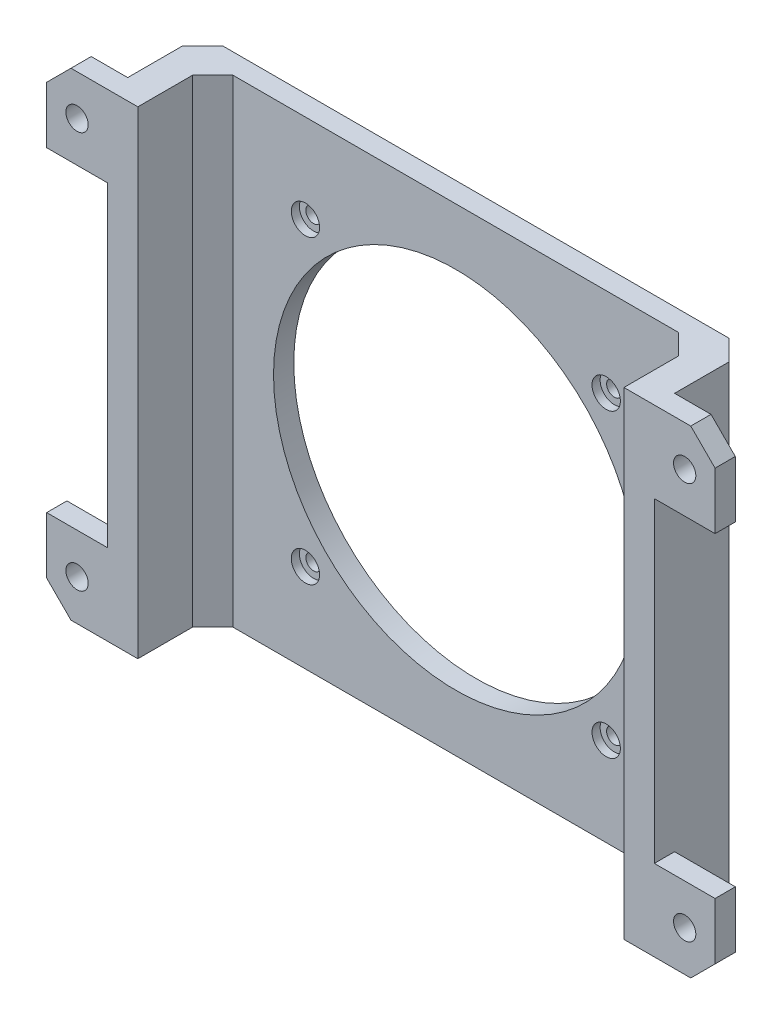
SolidWorks part; units mm, degrees
ref_plane "前视基准面" through (0, 0, 0) normal (0, 0, 1) x (1, 0, 0)
ref_plane "上视基准面" through (0, 0, 0) normal (0, 1, 0) x (1, 0, 0)
ref_plane "右视基准面" through (0, 0, 0) normal (1, 0, 0) x (0, 0, -1)
other "Configuration Table"
sketch "草图7" plane through (0, 0, 0) normal (0, 1, 0) x (1, 0, 0)
  line L0 (-67.5, 0) -> (67.5, 0)
  line L1 (67.5, 0) -> (67.5, -18.5)
  line L2 (67.5, -18.5) -> (82.5, -18.5)
  line L3 (82.5, -18.5) -> (82.5, -23.5)
  line L4 (82.5, -23.5) -> (60, -23.5)
  line L5 (60, -23.5) -> (60, -5)
  line L6 (60, -5) -> (-60, -5)
  line L7 (0, -5) -> (0, -28.5503) construction
  line L8 (-60, -23.5) -> (-60, -5)
  line L9 (-82.5, -23.5) -> (-60, -23.5)
  line L10 (-82.5, -18.5) -> (-82.5, -23.5)
  line L11 (-67.5, -18.5) -> (-82.5, -18.5)
  line L12 (-67.5, 0) -> (-67.5, -18.5)
  point P16 (0, 0)
  dimension "D1" = 135
  dimension "D2" = 5
  dimension "D3" = 7.5
  dimension "D4" = 5
  dimension "D5" = 23.5
  dimension "D6" = 165
extrude "凸台-拉伸5" add sketch "草图7" along normal blind 118
sketch "草图8" plane through (0, 0, 0) normal (0, 0, -1) x (-1, 0, 0)
  line L2 (-67.5, 0) -> (67.5, 0) construction
  circle A0 centre (0, 59) radius 45
  dimension "D1" = 90
  dimension "D2" = 59
extrude "切除-拉伸2" cut sketch "草图8" against normal blind 130
chamfer "倒角1" distance 6 angle 45 4 edges at (82.5, 118, 21) (82.5, 0, 21) (-82.5, 0, 21) (-82.5, 118, 21)
sketch "草图9" plane through (0, 0, 18.5) normal (0, 0, -1) x (-1, 0, 0)
  line L0 (-82.5, 112) -> (-82.5, 6) construction
  line L1 (-97.5, 20) -> (-67.5, 20)
  line L2 (-97.5, 20) -> (-97.5, 98)
  line L3 (-97.5, 98) -> (-67.5, 98)
  line L4 (-67.5, 20) -> (-67.5, 98)
  line L5 (-97.5, 20) -> (-67.5, 98) construction
  line L6 (-97.5, 98) -> (-67.5, 20) construction
  line L7 (-67.5, 118) -> (-67.5, 0) construction
  line L8 (-76.5, 0) -> (-67.5, 0) construction
  line L10 (0, 0) -> (0, 92.7135) construction
  line L11 (97.5, 98) -> (67.5, 20) construction
  line L12 (97.5, 20) -> (67.5, 98) construction
  line L13 (67.5, 20) -> (67.5, 98)
  line L14 (97.5, 98) -> (67.5, 98)
  line L15 (97.5, 20) -> (97.5, 98)
  line L16 (97.5, 20) -> (67.5, 20)
  point P0 (-82.5, 59)
  point P18 (82.5, 59)
  dimension "D1" = 20
extrude "切除-拉伸3" cut sketch "草图9" against normal blind 130
chamfer "倒角2" distance 5 angle 45 4 edges at (-67.5, 59, 0) (0, 0, 0) (0, 118, 0) (67.5, 59, 0)
chamfer "倒角3" distance 5 angle 45 2 edges at (-60, 59, 5) (60, 59, 5)
sketch "草图10" plane through (0, 0, 18.5) normal (0, 0, -1) x (-1, 0, 0)
  line L0 (67.5, 118) -> (67.5, 0) construction
  line L1 (67.5, 20) -> (82.5, 20) construction
  line L2 (82.5, 98) -> (67.5, 98) construction
  line L3 (67.5, 118) -> (67.5, 98) construction
  line L4 (-67.5, 98) -> (-82.5, 98) construction
  line L5 (-67.5, 0) -> (-67.5, 118) construction
  line L6 (-67.5, 20) -> (-67.5, 0) construction
  line L7 (-67.5, 20) -> (-82.5, 20) construction
  circle A0 centre (75, 10) radius 2.75
  circle A1 centre (-75, 10) radius 2.75
  circle A2 centre (-75, 108) radius 2.75
  circle A3 centre (75, 108) radius 2.75
  dimension "D1" = 5.5
  dimension "D2" = 7.5
  dimension "D3" = 10
  dimension "D4" = 10
  dimension "D5" = 7.5
  dimension "D6" = 10
  dimension "D7" = 7.5
  dimension "D8" = 7.5
  dimension "D9" = 10
extrude "切除-拉伸4" cut sketch "草图10" against normal through all
sketch "草图11" plane through (0, 0, 0) normal (0, 0, -1) x (-1, 0, 0)
  line L0 (-52.5, 59) -> (52.5, 59) construction
  line L1 (-37.1231, 96.1231) -> (37.1231, 21.8769) construction
  line L2 (-37.1231, 21.8769) -> (37.1231, 96.1231) construction
  circle A0 centre (0, 59) radius 52.5 construction
  point P10 (-37.1231, 96.1231)
  point P11 (-37.1231, 21.8769)
  point P12 (37.1231, 96.1231)
  point P13 (37.1231, 21.8769)
  dimension "D1" = 105
  dimension "D2" = 45
  dimension "D3" = 45
sketch "草图12" plane through (0, 0, 5) normal (0, 0, 1) x (1, 0, 0)
  line L0 (-52.5, 58.9971) -> (52.5, 58.9971) construction
  line L1 (-37.1231, 96.1202) -> (37.1231, 21.874) construction
  line L2 (-37.1231, 21.874) -> (37.1231, 96.1202) construction
  circle A0 centre (0, 58.9971) radius 52.5 construction
  point P8 (-37.1231, 96.1202)
  point P9 (-37.1231, 21.874)
  point P10 (37.1231, 96.1202)
  point P11 (37.1231, 21.874)
sketch "草图14" plane through (0, 0, 5) normal (0, 0, 1) x (1, 0, 0)
  circle A0 centre (-37.1231, 96.1231) radius 1.9
  circle A1 centre (-37.1231, 21.8769) radius 1.9
  circle A2 centre (37.1231, 21.8769) radius 1.9
  circle A3 centre (37.1231, 96.1231) radius 1.9
  dimension "D1" = 3.8
  dimension "D2" = 3.8
  dimension "D3" = 3.8
  dimension "D4" = 3.8
extrude "切除-拉伸5" cut sketch "草图14" against normal through all
sketch "草图15" plane through (0, 0, 5) normal (0, 0, 1) x (1, 0, 0)
  circle A0 centre (-37.1231, 96.1231) radius 3.5
  circle A1 centre (37.1231, 96.1231) radius 3.5
  circle A2 centre (37.1231, 21.8769) radius 3.5
  circle A3 centre (-37.1231, 21.8769) radius 3.5
  dimension "D1" = 7
  dimension "D2" = 7
  dimension "D3" = 7
  dimension "D4" = 7
extrude "切除-拉伸6" cut sketch "草图15" against normal blind 2
